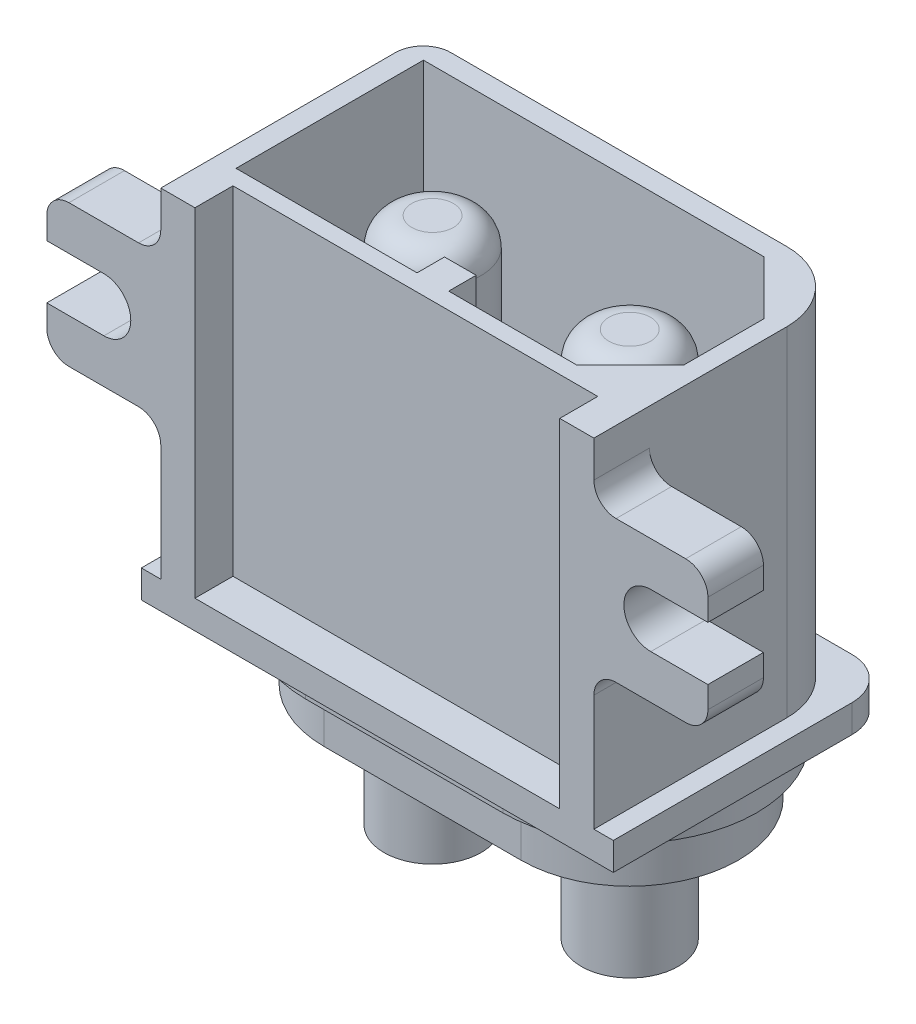
SolidWorks part; units mm, degrees
ref_plane "Front Plane" through (0, 0, 0) normal (0, 0, 1) x (1, 0, 0)
ref_plane "Top Plane" through (0, 0, 0) normal (0, 1, 0) x (1, 0, 0)
ref_plane "Right Plane" through (0, 0, 0) normal (1, 0, 0) x (0, 0, -1)
sketch "Sketch1" plane through (0, 0, 0) normal (0, 1, 0) x (1, 0, 0)
  line L0 (8.8642, 1.7532) -> (8.8642, -5.1968)
  line L1 (-5.7358, 4.2532) -> (6.3642, 4.2532)
  line L2 (-6.7358, 3.2532) -> (-6.7358, -5.1968)
  line L3 (-6.7358, -5.1968) -> (8.8642, -5.1968)
  arc A0 (-5.7358, 4.2532) -> (-6.7358, 3.2532) centre (-5.7358, 3.2532) ccw
  arc A1 (8.8642, 1.7532) -> (6.3642, 4.2532) centre (6.3642, 1.7532) ccw
  point P5 (-6.7358, 4.2532)
  dimension "D3" = 1
  dimension "D4" = 2.5
  dimension "D1" = 9.45
  dimension "D2" = 15.6
extrude "Boss-Extrude1" add sketch "Sketch1" along normal blind 13.2
sketch "Sketch2" plane through (0, 13.2, 0) normal (0, 1, 0) x (1, 0, 0)
  line L0 (-5.9958, 3.5232) -> (-5.9958, -3.2268)
  line L1 (-5.9958, -3.2268) -> (0.5242, -3.2268)
  line L2 (-5.9958, 0.1482) -> (9.5058, 0.1482) construction
  line L3 (8.2042, 1.5982) -> (8.2042, -1.3018)
  line L4 (8.2042, -1.3018) -> (6.2792, -3.2268)
  line L5 (6.2792, 3.5232) -> (-5.9958, 3.5232)
  line L7 (6.3642, 4.2532) -> (-5.7358, 4.2532) construction
  line L8 (-6.7358, 3.2532) -> (-6.7358, -5.1968) construction
  line L9 (8.2042, 1.5982) -> (6.2792, 3.5232)
  line L10 (1.6642, -3.2268) -> (6.2792, -3.2268)
  line L12 (0.5242, -3.2268) -> (0.5242, -2.2368)
  line L13 (0.5242, -2.2368) -> (1.6642, -2.2368)
  line L14 (1.6642, -3.2268) -> (1.6642, -2.2368)
  dimension "D2" = 0.73
  dimension "D3" = 0.74
  dimension "D4" = 14.2
  dimension "D5" = 2.9
  dimension "D1" = 6.75
  dimension "D6" = 1.45
  dimension "D7" = 1.14
  dimension "D8" = 8.4
  dimension "D9" = 0.99
extrude "Cut-Extrude1" cut sketch "Sketch2" against normal blind 8.6
sketch "Sketch3" plane through (0, 4.6, 0) normal (0, 1, 0) x (1, 0, 0)
  line L0 (-6.7778, 0.3432) -> (8.8642, 0.3432) construction
  line L1 (-6.7358, 3.2532) -> (-6.7358, -5.1968) construction
  line L3 (8.8642, -5.1968) -> (8.8642, 1.7532) construction
  line L7 (6.3642, 4.2532) -> (-5.7358, 4.2532) construction
  circle A0 centre (-2.4858, 0.3432) radius 1.75
  circle A1 centre (4.6142, 0.3432) radius 1.75
  dimension "D1" = 3.5
  dimension "D2" = 3.5
  dimension "D3" = 4.25
  dimension "D4" = 4.25
  dimension "D5" = 3.91
extrude "Boss-Extrude2" add sketch "Sketch3" along normal offset from surface 1.5 and the other way offset from surface (11.9 mm away) 7.3 separate body up to face at (2.1352, 13.2, 1.0038) other way up to face at (0.8659, 0, -0.6407)
sketch "Sketch4" plane through (0, 13.2, 0) normal (0, 1, 0) x (1, 0, 0)
  line L0 (-6.7358, -5.1968) -> (8.8642, -5.1968) construction
  line L1 (-5.5058, -5.1968) -> (7.6342, -5.1968)
  line L2 (-5.5058, -5.1968) -> (-5.5058, -3.8268)
  line L3 (-5.5058, -3.8268) -> (7.6342, -3.8268)
  line L4 (7.6342, -5.1968) -> (7.6342, -3.8268)
  line L5 (-6.7358, 3.2532) -> (-6.7358, -5.1968) construction
  dimension "D1" = 13.14
  dimension "D2" = 1.23
  dimension "D3" = 1.37
extrude "Cut-Extrude2" cut sketch "Sketch4" against normal blind 12.18
sketch "Sketch5" plane through (0, 0, 0) normal (0, -1, 0) x (1, 0, 0)
  line L1 (-6.7358, 5.1968) -> (8.8642, 5.1968) construction
  line L2 (-6.7358, -3.2532) -> (-6.7358, 5.1968) construction
  line L5 (-7.4358, 5.1968) -> (9.5642, 5.1968)
  line L6 (-7.4358, 5.1968) -> (-7.4358, -3.4032)
  line L7 (-5.9358, -4.9032) -> (8.0642, -4.9032)
  line L8 (9.5642, 5.1968) -> (9.5642, -3.4032)
  arc A0 (8.0642, -4.9032) -> (9.5642, -3.4032) centre (8.0642, -3.4032) ccw
  arc A1 (-7.4358, -3.4032) -> (-5.9358, -4.9032) centre (-5.9358, -3.4032) ccw
  point P6 (9.5642, -4.9032)
  point P10 (-7.4358, -4.9032)
  dimension "D4" = 1.5
  dimension "D1" = 17
  dimension "D2" = 10.1
  dimension "D3" = 0.7
extrude "Boss-Extrude3" add sketch "Sketch5" against normal blind 1
sketch "Sketch6" plane through (0, 0, 0) normal (0, -1, 0) x (1, 0, 0)
  line L0 (-2.4858, -0.3432) -> (4.6142, -0.3432) construction
  line L1 (-2.4858, 4.2268) -> (4.6142, 4.2268)
  line L2 (-2.4858, -4.9132) -> (4.6142, -4.9132)
  arc A0 (-2.4858, 4.2268) -> (-2.4858, -4.9132) centre (-2.4858, -0.3432) ccw
  arc A1 (4.6142, -4.9132) -> (4.6142, 4.2268) centre (4.6142, -0.3432) ccw
  point P4 (1.0642, -0.3432)
  dimension "D1" = 9.14
extrude "Boss-Extrude4" add sketch "Sketch6" along normal offset from surface (1.1 mm away) 14.3 up to face at (0.9452, 13.2, 1.4203)
sketch "Sketch7" plane through (0, -1.1, 0) normal (0, -1, 0) x (-1, 0, 0)
  line L0 (2.4858, 0.3432) -> (-4.6142, 0.3432) construction
  line L1 (2.4858, -3.5668) -> (-4.6142, -3.5668)
  line L2 (2.4858, 4.2532) -> (-4.6142, 4.2532)
  arc A0 (2.4858, -3.5668) -> (2.4858, 4.2532) centre (2.4858, 0.3432) ccw
  arc A1 (-4.6142, 4.2532) -> (-4.6142, -3.5668) centre (-4.6142, 0.3432) ccw
  circle A2 centre (2.4858, 0.3432) radius 2.5
  circle A3 centre (-4.6142, 0.3432) radius 2.5
  point P4 (-1.0642, 0.3432)
  dimension "D2" = 5
  dimension "D3" = 5
  dimension "D1" = 7.82
extrude "Boss-Extrude5" add sketch "Sketch7" along normal offset from surface (1.81 mm away) 16.11 up to face at (0.9452, 13.2, 1.4203)
sketch "Sketch8" plane through (0, -7.3, 0) normal (0, -1, 0) x (1, 0, 0)
  circle A0 centre (4.6142, -0.3432) radius 1.15
  circle A1 centre (-2.4858, -0.3432) radius 1.15
  dimension "D1" = 2.3
  dimension "D2" = 2.3
extrude "Cut-Extrude3" cut sketch "Sketch8" against normal blind 7
sketch "Sketch9" plane through (0, 0, 5.1968) normal (0, 0, 1) x (1, 0, 0)
  line L0 (-6.7358, 13.2) -> (-6.7358, 1) construction
  line L1 (-7.5358, 11.09) -> (-10.0422, 11.09)
  line L2 (-6.7358, 11.89) -> (-6.7358, 5.18)
  line L3 (-7.5358, 5.98) -> (-10.0422, 5.98)
  line L4 (-10.8422, 10.29) -> (-10.8422, 9.5044)
  line L5 (1.0642, 13.2) -> (1.0642, -2.91) construction
  line L6 (7.6342, 13.2) -> (-5.5058, 13.2) construction
  line L7 (-2.4858, -2.91) -> (4.6142, -2.91) construction
  line L8 (-6.7358, 13.2) -> (-5.5058, 13.2) construction
  line L9 (-8.7858, 7.5656) -> (-10.8422, 7.5656)
  line L10 (-8.7858, 9.5044) -> (-10.8422, 9.5044)
  line L11 (-10.8422, 7.5656) -> (-10.8422, 6.78)
  line L12 (12.9705, 7.5656) -> (12.9705, 6.78)
  line L13 (10.9142, 9.5044) -> (12.9705, 9.5044)
  line L14 (10.9142, 7.5656) -> (12.9705, 7.5656)
  line L15 (12.9705, 10.29) -> (12.9705, 9.5044)
  line L16 (9.6642, 5.98) -> (12.1705, 5.98)
  line L17 (8.8642, 11.89) -> (8.8642, 5.18)
  line L18 (9.6642, 11.09) -> (12.1705, 11.09)
  arc A0 (-8.7858, 7.5656) -> (-8.7858, 9.5044) centre (-8.7858, 8.535) ccw
  arc A1 (-10.0422, 5.98) -> (-10.8422, 6.78) centre (-10.0422, 6.78) cw
  arc A2 (-10.0422, 11.09) -> (-10.8422, 10.29) centre (-10.0422, 10.29) ccw
  arc A3 (-6.7358, 5.18) -> (-7.5358, 5.98) centre (-7.5358, 5.18) ccw
  arc A4 (-7.5358, 11.09) -> (-6.7358, 11.89) centre (-7.5358, 11.89) ccw
  arc A5 (9.6642, 11.09) -> (8.8642, 11.89) centre (9.6642, 11.89) cw
  arc A6 (8.8642, 5.18) -> (9.6642, 5.98) centre (9.6642, 5.18) cw
  arc A7 (12.1705, 11.09) -> (12.9705, 10.29) centre (12.1705, 10.29) cw
  arc A8 (12.1705, 5.98) -> (12.9705, 6.78) centre (12.1705, 6.78) ccw
  arc A9 (10.9142, 7.5656) -> (10.9142, 9.5044) centre (10.9142, 8.535) cw
  point P14 (-6.1208, 13.2)
  point P28 (-6.7358, 11.09)
  point P46 (8.8642, 11.09)
  dimension "D5" = 0.8
  dimension "D6" = 0.8
  dimension "D1" = 5.11
  dimension "D2" = 7.22
  dimension "D3" = 2.555
  dimension "D4" = 9.85
extrude "Boss-Extrude6" add sketch "Sketch9" against normal blind 2
fillet "Fillet1" radius 1 2 edges at (4.6142, 11.7, 1.4068) (-2.4858, 11.7, 1.4068)
